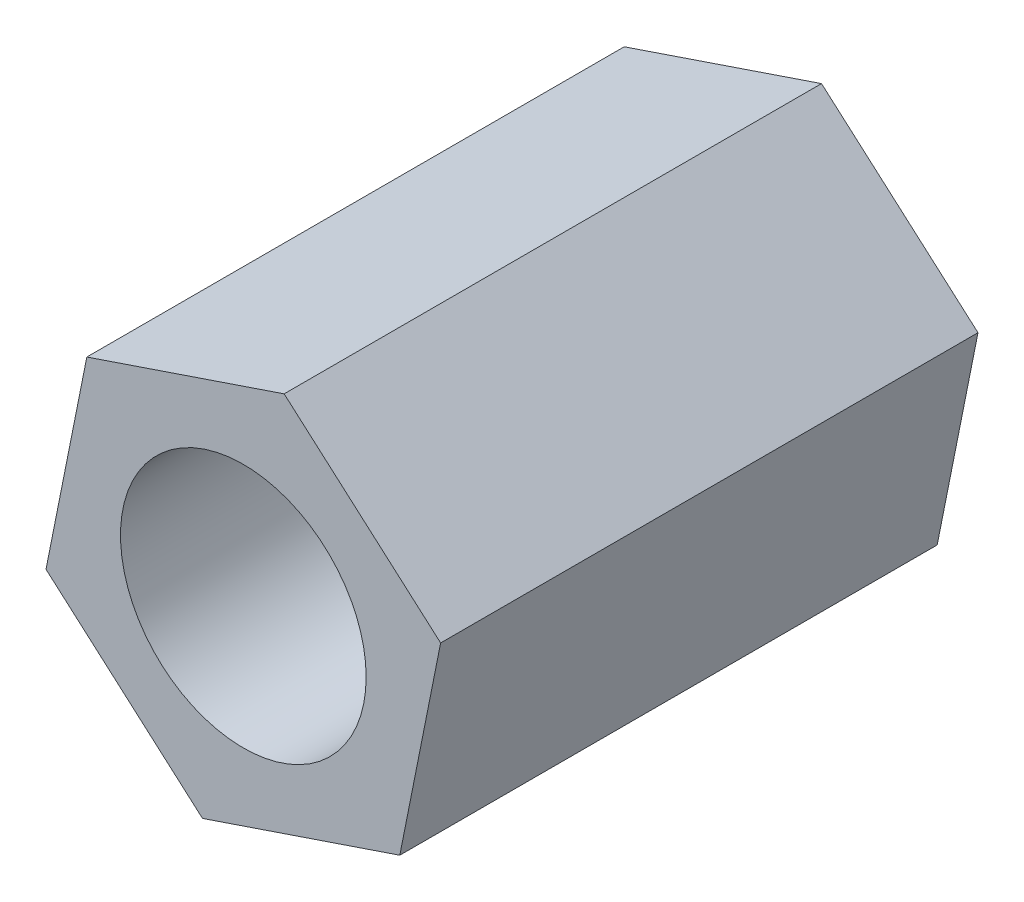
SolidWorks part; units mm, degrees
ref_plane "前视基准面" through (0, 0, 0) normal (0, 0, 1) x (1, 0, 0)
ref_plane "上视基准面" through (0, 0, 0) normal (0, 1, 0) x (1, 0, 0)
ref_plane "右视基准面" through (0, 0, 0) normal (1, 0, 0) x (0, 0, -1)
sketch "草图1" plane through (0, 0, 0) normal (0, 0, 1) x (1, 0, 0)
  line L1 (2.0384, -1.7911) -> (2.5704, 0.8698)
  line L2 (2.5704, 0.8698) -> (0.5319, 2.6609)
  line L3 (0.5319, 2.6609) -> (-2.0384, 1.7911)
  line L4 (-2.0384, 1.7911) -> (-2.5704, -0.8698)
  line L5 (-2.5704, -0.8698) -> (-0.5319, -2.6609)
  line L6 (-0.5319, -2.6609) -> (2.0384, -1.7911)
  circle A0 centre (0, 0) radius 2.35 construction
  circle A1 centre (0, 0) radius 1.6
  dimension "D1" = 3.2
  dimension "D2" = 4.7
extrude "凸台-拉伸1" add sketch "草图1" along normal blind 7
